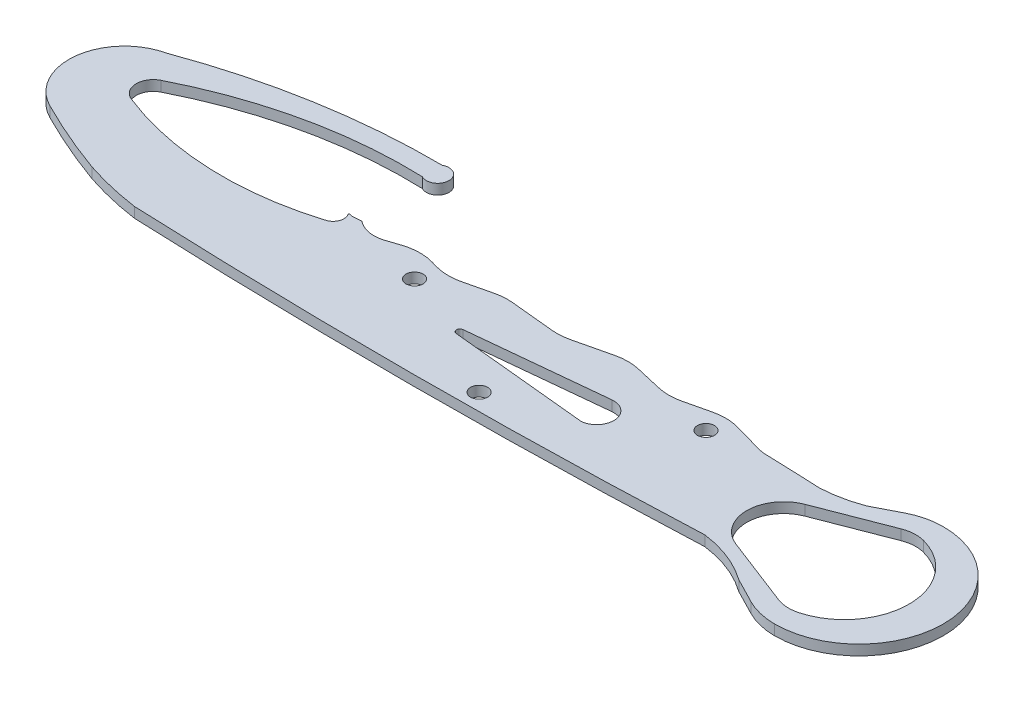
SolidWorks part; units mm, degrees
material "Titanium"
ref_plane "Front Plane" through (0, 0, 0) normal (0, 0, 1) x (1, 0, 0)
ref_plane "Top Plane" through (0, 0, 0) normal (0, 1, 0) x (1, 0, 0)
ref_plane "Right Plane" through (0, 0, 0) normal (1, 0, 0) x (0, 0, -1)
sketch "Sketch1" plane through (0, 0, 0) normal (0, 1, 0) x (1, 0, 0)
  line L5 (-41.7962, 2.3828) -> (-37.7333, 3.7269)
  line L6 (-28.9191, 3.9139) -> (-27.2289, 3.4333)
  line L7 (-7.348, -8.6513) -> (32.252, -4.6713)
  line L8 (33.1443, -14.6308) -> (-7.346, -10.6414)
  line L10 (86.875, -2.9183) -> (107.1849, 4.9355)
  line L11 (-941.6764, -12.9914) -> (-85.0313, -12.9914) construction
  line L12 (96.3253, -31.6756) -> (103.5993, -35.422)
  line L13 (86.875, -23.0645) -> (107.1849, -30.9183)
  line L14 (96.3253, 5.6928) -> (103.5993, 9.4392)
  line L16 (-19.6633, 3.2664) -> (-11.9199, 5.1035)
  line L17 (-6.9919, 5.4368) -> (5.9519, 4.1662)
  line L18 (10.8799, 4.4995) -> (21.4055, 6.9967)
  line L19 (28.2616, 7.0129) -> (35.995, 5.2168)
  line L20 (42.8511, 5.233) -> (49.966, 6.921)
  line L21 (57.4556, 6.7754) -> (66.1893, 4.3414)
  line L22 (-130.1368, 12.1629) -> (-42465.6882, 26513.1431) construction
  line L219 (-83.7296, -12.9914) -> (49058.3236, -12.9914) construction
  line L231 (-84.3476, -16.5) -> (-100.8553, -6.1666) construction
  arc A14 (68.5712, 3.9789) -> (84.8428, 3.3483) centre (39.4249, -958.3696) cw
  arc A15 (32.252, -4.6713) -> (33.1443, -14.6308) centre (32.752, -9.6463) cw
  arc A16 (-7.346, -10.6414) -> (-7.348, -8.6513) centre (-7.248, -9.6463) cw
  arc A17 (113.3661, 5.2715) -> (127.4003, -12.9914) centre (108.5003, -12.9914) cw
  arc A18 (79.9703, -12.9914) -> (86.875, -2.9183) centre (90.7703, -12.9914) cw
  arc A19 (112.6994, -37.6416) -> (112.6994, 11.6588) centre (112.7703, -12.9914) ccw
  arc A20 (84.8428, 3.3483) -> (96.3253, 5.6928) centre (83.1216, 41.0686) ccw
  arc A21 (103.5993, -35.422) -> (112.6994, -37.6416) centre (112.7569, -17.6414) ccw
  arc A22 (103.5993, 9.4392) -> (112.6994, 11.6588) centre (112.7569, -8.3414) cw
  arc A23 (113.3661, 5.2715) -> (107.1849, 4.9355) centre (110.7916, -4.3914) ccw
  arc A24 (113.3661, -31.2543) -> (107.1849, -30.9183) centre (110.7916, -21.5914) cw
  arc A25 (113.3661, -31.2543) -> (127.4003, -12.9914) centre (108.5003, -12.9914) ccw
  arc A26 (79.9703, -12.9914) -> (86.875, -23.0645) centre (90.7703, -12.9914) ccw
  arc A29 (66.1893, 4.3414) -> (68.5712, 3.9789) centre (68.8739, 13.9743) ccw
  arc A31 (49.966, 6.921) -> (57.4556, 6.7754) centre (53.4286, -7.6739) cw
  arc A32 (42.8511, 5.233) -> (35.995, 5.2168) centre (39.3885, 19.8279) cw
  arc A33 (28.2616, 7.0129) -> (21.4055, 6.9967) centre (24.8681, -7.5982) ccw
  arc A34 (5.9519, 4.1662) -> (10.8799, 4.4995) centre (7.4173, 19.0944) ccw
  arc A35 (-6.9919, 5.4368) -> (-11.9199, 5.1035) centre (-8.4574, -9.4914) ccw
  arc A36 (-27.2289, 3.4333) -> (-19.6633, 3.2664) centre (-23.1259, 17.8612) ccw
  arc A37 (-28.9191, 3.9139) -> (-37.7333, 3.7269) centre (-33.022, -10.514) ccw
  circle A122 centre (-27.2289, -2.9272) radius 2.5
  circle A129 centre (10.8799, -22.1693) radius 2.5
  circle A132 centre (53.72, 1.3233) radius 2.5
  arc A134 (-120.5992, 18.0304) -> (-51.9753, 29.907) centre (-54.0766, -162.1469) cw
  arc A136 (-51.9753, 29.907) -> (-51.9504, 24.0968) centre (-50.4009, 27.0086) cw
  arc A138 (-41.7962, 2.3828) -> (-49.587, 4.011) centre (-44.106, 10.784) cw
  arc A142 (-49.587, 4.011) -> (-52.6119, 3.8293) centre (-54.1564, 54.8219) cw
  arc A143 (-53.4347, 3.9115) -> (-55.0346, -1.0239) centre (-55.977, 2.0086) cw
  arc A144 (-53.4347, 3.9115) -> (-52.6119, 3.8293) centre (-53.06, 3.5035) cw
  arc A145 (-114.6483, 10.2917) -> (-51.9504, 24.0968) centre (-56.572, -104.1921) cw
  arc A146 (-102.7684, -21.6987) -> (-124.4585, -12.3443) centre (-38.5763, 156.9677) cw
  arc A149 (-55.0346, -1.0239) -> (-114.2338, 1.2443) centre (-81.424, 83.8931) cw
  arc A153 (-124.4585, -12.3443) -> (-120.5992, 18.0304) centre (-117.1045, 2.1538) cw
  arc A155 (-114.2338, 1.2443) -> (-114.6483, 10.2917) centre (-112.4009, 5.8615) cw
  arc A156 (-86.5105, -25.5105) -> (79.9703, -25.279) centre (-5.8947, 1861.7248) ccw
  arc A157 (79.9703, -25.279) -> (96.3253, -31.6756) centre (75.4421, -60.9633) cw
  arc A158 (-86.5105, -25.5105) -> (-102.7684, -21.6987) centre (-73.3612, 67.1508) cw
  point P1 (-3.7296, -22.3707)
  point P20 (-133.2314, 4.2029)
  point P23 (97.03, 1.0086)
  point P45 (106.1516, -36.7365)
  point P59 (137.4206, -12.9914)
  point P64 (0, 0)
  point P69 (53.042, -13.2568)
  point P70 (45.6514, -13.1451)
  point P79 (39.4249, 4.4201)
  point P85 (8.4437, 3.9215)
  point P91 (-23.4679, 2.3638)
  point P95 (35.5014, -13.1496)
  point P96 (-2.5846, -13.0003)
  point P97 (-27.2289, -2.9272)
  point P98 (0, 0)
  point P99 (10.8739, -23.0734)
  point P100 (0, 0)
  point P102 (6.6112, -12.9914)
  point P103 (0, 0)
  point P104 (6.6139, -23.0645)
  point P105 (0, 0)
  point P106 (0, 0)
  point P107 (0, 0)
  point P108 (10.8799, -22.1693)
  point P109 (0, 0)
  point P369 (53.72, 7.3233)
  point P410 (66.7783, -13.1451)
  dimension "D2" = 10
  dimension "D3" = 1
  dimension "D4" = 5
  dimension "D6" = 48.2001
  dimension "D7" = 40
  dimension "D15" = 10
  dimension "D17" = 9.3
  dimension "D18" = 17.2
  dimension "D5" = 270.652
  dimension "D19" = 18.9
  dimension "D20" = 10.8
  dimension "D23" = 47.43
  dimension "D24" = 36.5258
  dimension "D27" = 25
  dimension "D28" = 62
  dimension "D25" = 40
  dimension "D26" = 5
  dimension "D9" = 14
  dimension "D11" = 22
  dimension "D12" = 72.9984
  dimension "D21" = 21.7755
extrude "Boss-Extrude1" add sketch "Sketch1" along normal mid plane 3
